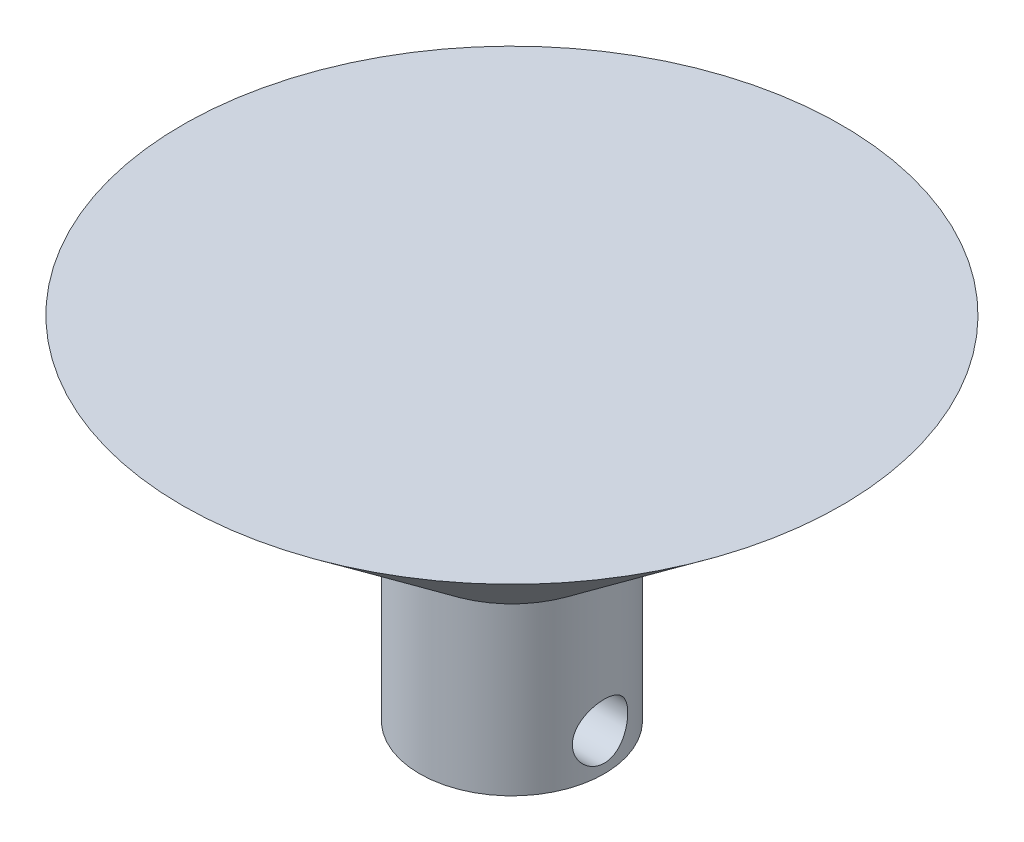
SolidWorks part; units mm, degrees
ref_plane "Front Plane" through (0, 0, 0) normal (0, 0, 1) x (1, 0, 0)
ref_plane "Top Plane" through (0, 0, 0) normal (0, 1, 0) x (1, 0, 0)
ref_plane "Right Plane" through (0, 0, 0) normal (1, 0, 0) x (0, 0, -1)
sketch "Sketch1" plane through (0, 0, 0) normal (0, 1, 0) x (1, 0, 0)
  circle A0 centre (0, 0) radius 5
  dimension "D1" = 10
extrude "body" add sketch "Sketch1" along normal blind 9
sketch "Sketch2" plane through (0, 0, 0) normal (1, 0, 0) x (0, 0, -1)
  circle A0 centre (0, 2) radius 1.5
  dimension "D1" = 2
  dimension "D2" = 3
extrude "pin insert" cut sketch "Sketch2" against normal through all and the other way through all
ref_plane "contact plane" through (0, 19, 0) normal (0, 1, 0) x (1, 0, 0)
sketch "head SA" plane through (0, 19, 0) normal (0, 1, 0) x (1, 0, 0)
  circle A0 centre (0, 0) radius 17.841
  dimension "D1" = 35.682
loft "cone" add profiles "head SA" section "head SA" section face at (0, 9, 5)
